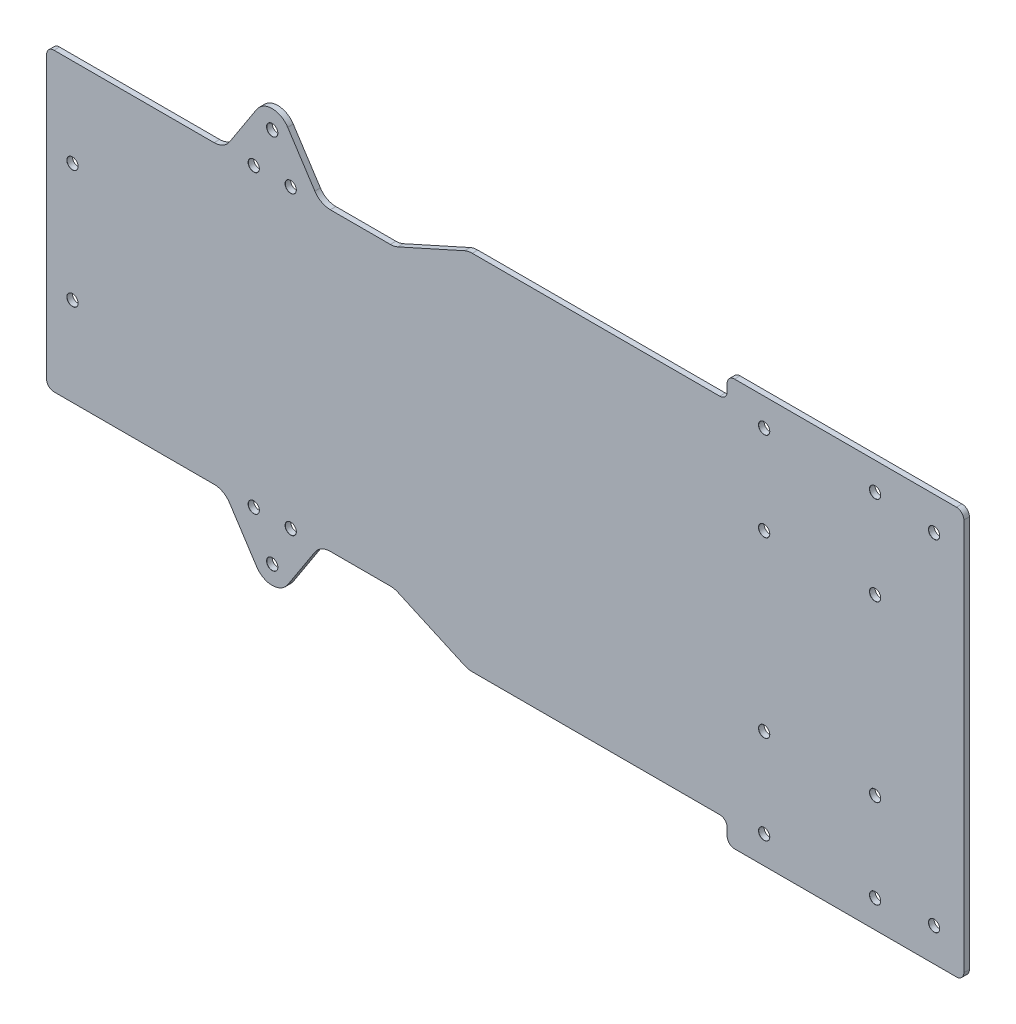
SolidWorks part; units mm, degrees
material "AISI 1045 Steel, cold drawn"
ref_plane "Front Plane" through (0, 0, 0) normal (0, 0, 1) x (1, 0, 0)
ref_plane "Top Plane" through (0, 0, 0) normal (0, 1, 0) x (1, 0, 0)
ref_plane "Right Plane" through (0, 0, 0) normal (1, 0, 0) x (0, 0, -1)
sketch "Sketch1" plane through (0, 0, 0) normal (0, 0, 1) x (1, 0, 0)
  line L0 (0, 0) -> (-124, 0)
  line L1 (-124, 0) -> (-124, -38)
  line L2 (-122, -40) -> (-78.7134, -40)
  line L3 (-74.5212, -42.2751) -> (-67.1922, -53.5504)
  line L4 (-58.8078, -53.5504) -> (-51.4788, -42.2751)
  line L5 (-47.2866, -40) -> (-31.0732, -40)
  line L6 (-29.0214, -40.4404) -> (-10.9786, -48.5596)
  line L7 (-8.9268, -49) -> (58, -49)
  line L8 (60, -51) -> (60, -53)
  line L9 (62, -55) -> (122, -55)
  line L10 (124, -53) -> (124, 0)
  line L11 (124, 0) -> (0, 0)
  line L12 (-76, -40) -> (-50, -40) construction
  line L13 (-63, -40) -> (-63, -60) construction
  arc A0 (-10.9786, -48.5596) -> (-8.9268, -49) centre (-8.9268, -44) ccw
  arc A1 (-31.0732, -40) -> (-29.0214, -40.4404) centre (-31.0732, -45) cw
  arc A2 (-51.4788, -42.2751) -> (-47.2866, -40) centre (-47.2866, -45) cw
  arc A3 (-67.1922, -53.5504) -> (-58.8078, -53.5504) centre (-63, -50.8255) ccw
  arc A4 (-78.7134, -40) -> (-74.5212, -42.2751) centre (-78.7134, -45) cw
  arc A5 (122, -55) -> (124, -53) centre (122, -53) ccw
  arc A6 (60, -53) -> (62, -55) centre (62, -53) ccw
  arc A7 (58, -49) -> (60, -51) centre (58, -51) cw
  arc A8 (-124, -38) -> (-122, -40) centre (-122, -38) ccw
  point P17 (-10, -49)
  point P20 (-30, -40)
  point P32 (124, -55)
  point P35 (60, -55)
  point P38 (60, -49)
  point P41 (-124, -40)
  dimension "D11" = 5
  dimension "D12" = 2
  dimension "D1" = 248
  dimension "D2" = 40
  dimension "D3" = 48
  dimension "D4" = 26
  dimension "D5" = 20
  dimension "D6" = 20
  dimension "D7" = 6
  dimension "D8" = 64
  dimension "D9" = 55
  dimension "D10" = 70
extrude "Boss-Extrude2" add sketch "Sketch1" against normal blind 1.5
mirror "Mirror1" about plane through (0, 0, -1.5) normal (0, 1, 0) of "Boss-Extrude2"
sketch "Sketch3" plane through (0, 0, 0) normal (0, 0, 1) x (1, 0, 0)
  line L0 (-124, 0) -> (124, 0) construction
  line L1 (-124, 38) -> (-124, -38) construction
  line L2 (124, -53) -> (124, 53) construction
  line L3 (-124, 16) -> (-117, 16) construction
  line L4 (124, 46) -> (115.95, 46) construction
  line L5 (124, -46) -> (115.95, -46) construction
  line L6 (-124, -16) -> (-117, -16) construction
  point P7 (-117, 16)
  point P9 (115.95, 46)
  point P10 (115.95, -46)
  point P13 (-117, -16)
  point P18 (-117, 16)
  point P22 (115.95, 46)
  dimension "D1" = 7
  dimension "D2" = 16
  dimension "D3" = 232.95
  dimension "D4" = 46
hole_wizard "Ø3.0 (3) Diameter Hole2" positions "Sketch3" profile "Sketch7" hole size "Ø3.0" standard "ISO"
sketch "Sketch7" plane through (115.95, 46, 0) normal (1, 0, 0) x (0, -1, 0)
  line L0 (0, 0) -> (0, 4.9013)
  line L1 (0, 4.9013) -> (1.5, 4)
  line L2 (1.5, 4) -> (1.5, 0.025)
  line L3 (1.5, 0.025) -> (1.525, 0)
  line L5 (1.525, 0) -> (0, 0)
  line L6 (-1.5, 0.025) -> (-1.525, 0) construction
  line L10 (0, 4.9013) -> (-1.5, 4) construction
  line L11 (0, -6.35) -> (0, 107.95) construction
  dimension "Hole Dia." = 3
  dimension "Hole Depth" = 4
  dimension "Near C'Sink Dia." = 3.05
  dimension "Near C'Sink Angle" = 90
  dimension "Drill Angle" = 118
sketch "Sketch8" plane through (0, 0, 0) normal (0, 0, 1) x (1, 0, 0)
  line L0 (-78.7134, 40) -> (-47.2866, 40) construction
  line L1 (-63, 55.8255) -> (-63, 50.8255) construction
  line L2 (0, 0) -> (-124, 0) construction
  line L3 (-124, 38) -> (-124, -38) construction
  arc A1 (-58.8078, 53.5504) -> (-67.1922, 53.5504) centre (-63, 50.8255) ccw construction
  point P5 (-63, 50.8255)
  point P9 (-68, 40)
  point P10 (-58, 40)
  point P12 (-63, 40)
  point P18 (-58, -40)
  point P19 (-68, -40)
  point P20 (-63, -50.8255)
  point P23 (-63, 50.8255)
  dimension "D1" = 5
  dimension "D2" = 5
hole_wizard "Ø3.0 (3) Diameter Hole3" positions "Sketch8" profile "Sketch9" hole size "Ø3.0" standard "ISO"
sketch "Sketch9" plane through (-63, 50.8255, 0) normal (1, 0, 0) x (0, -1, 0)
  line L0 (0, 0) -> (0, 4.9013)
  line L1 (0, 4.9013) -> (1.5, 4)
  line L2 (1.5, 4) -> (1.5, 0.025)
  line L3 (1.5, 0.025) -> (1.525, 0)
  line L5 (1.525, 0) -> (0, 0)
  line L6 (-1.5, 0.025) -> (-1.525, 0) construction
  line L10 (0, 4.9013) -> (-1.5, 4) construction
  line L11 (0, -6.35) -> (0, 107.95) construction
  dimension "Hole Dia." = 3
  dimension "Hole Depth" = 4
  dimension "Near C'Sink Dia." = 3.05
  dimension "Near C'Sink Angle" = 90
  dimension "Drill Angle" = 118
sketch "Sketch10" plane through (0, 0, 0) normal (0, 0, 1) x (1, 0, 0)
  line L0 (62, 55) -> (122, 55) construction
  line L1 (60, 51) -> (60, 53) construction
  line L2 (0, 0) -> (124, 0) construction
  line L3 (124, -53) -> (124, 53) construction
  point P0 (100, 47.5)
  point P1 (70, 47.5)
  point P2 (70, 23.5)
  point P3 (100, 23.5)
  point P6 (100, -47.5)
  point P7 (100, -23.5)
  point P8 (70, -23.5)
  point P9 (70, -47.5)
  dimension "D1" = 7.5
  dimension "D2" = 30
  dimension "D3" = 24
  dimension "D4" = 10
hole_wizard "Ø3.0 (3) Diameter Hole4" positions "Sketch10" profile "Sketch11" hole size "Ø3.0" standard "ISO"
sketch "Sketch11" plane through (100, 47.5, 0) normal (1, 0, 0) x (0, -1, 0)
  line L0 (0, 0) -> (0, 4.9013)
  line L1 (0, 4.9013) -> (1.5, 4)
  line L2 (1.5, 4) -> (1.5, 0.025)
  line L3 (1.5, 0.025) -> (1.525, 0)
  line L5 (1.525, 0) -> (0, 0)
  line L6 (-1.5, 0.025) -> (-1.525, 0) construction
  line L10 (0, 4.9013) -> (-1.5, 4) construction
  line L11 (0, -6.35) -> (0, 107.95) construction
  dimension "Hole Dia." = 3
  dimension "Hole Depth" = 4
  dimension "Near C'Sink Dia." = 3.05
  dimension "Near C'Sink Angle" = 90
  dimension "Drill Angle" = 118
